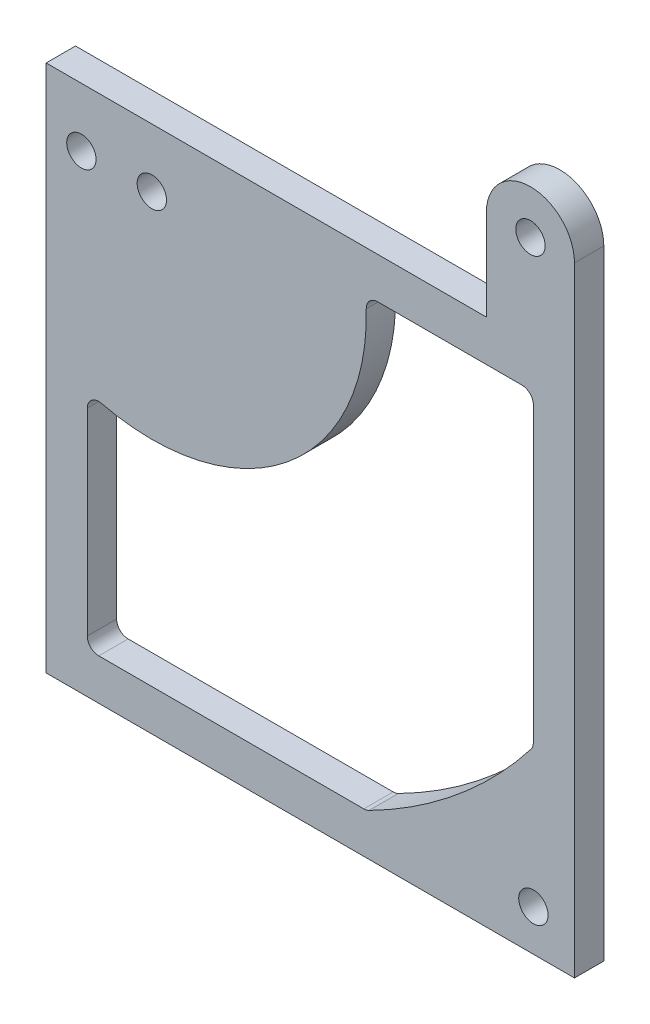
SolidWorks part; units mm, degrees
ref_plane "Front Plane" through (0, 0, 0) normal (0, 0, 1) x (1, 0, 0)
ref_plane "Top Plane" through (0, 0, 0) normal (0, 1, 0) x (1, 0, 0)
ref_plane "Right Plane" through (0, 0, 0) normal (1, 0, 0) x (0, 0, -1)
sketch "Sketch1" plane through (0, 0, 0) normal (0, 0, 1) x (1, 0, 0)
  line L1 (-57.15, -57.15) -> (57.15, -57.15)
  line L2 (-57.15, -57.15) -> (-57.15, 57.15)
  line L3 (-57.15, 57.15) -> (38.1, 57.15)
  line L4 (57.15, -57.15) -> (57.15, 76.835)
  line L5 (57.15, -57.15) -> (-57.15, 57.15) construction
  line L19 (47.625, 76.835) -> (47.625, 48.26) construction
  line L22 (38.1, 76.835) -> (38.1, 57.15)
  line L24 (-45.7715, -48.2506) -> (11.5718, -48.2506)
  line L25 (-48.26, -45.7621) -> (-48.26, -3.0766)
  line L27 (48.26, -17.4506) -> (48.26, 45.7715)
  line L30 (14.5859, 48.26) -> (45.7715, 48.26)
  line L31 (48.26, -17.4506) -> (48.26, -48.2506) construction
  line L32 (11.5718, -48.2506) -> (48.26, -48.2506) construction
  circle A17 centre (-49.53, 44.45) radius 3.175
  circle A18 centre (-34.29, 44.45) radius 3.175
  arc A34 (-45.1872, -0.6577) -> (12.0984, 45.7043) centre (-34.29, 44.45) ccw
  arc A36 (12.6995, -47.9804) -> (47.7402, -18.9727) centre (-34.29, 44.45) ccw
  arc A37 (-45.1872, -0.6577) -> (-48.26, -3.0766) centre (-45.7715, -3.0766) ccw
  arc A38 (-45.7715, -48.2506) -> (-48.26, -45.7621) centre (-45.7715, -45.7621) cw
  arc A39 (12.6995, -47.9804) -> (11.5718, -48.2506) centre (11.5718, -45.7621) cw
  arc A40 (48.26, -17.4506) -> (47.7402, -18.9727) centre (45.7715, -17.4506) cw
  arc A41 (45.7715, 48.26) -> (48.26, 45.7715) centre (45.7715, 45.7715) cw
  arc A42 (12.0984, 45.7043) -> (14.5859, 48.26) centre (14.5859, 45.7715) cw
  circle A44 centre (48.26, -48.2506) radius 3.175
  circle A45 centre (47.625, 76.835) radius 3.175
  arc A46 (38.1, 76.835) -> (57.15, 76.835) centre (47.625, 76.835) cw
  point P0 (0, 0)
  point P16 (0, 0)
  dimension "D4" = 6.35
  dimension "D5" = 6.35
  dimension "D6" = 8.89
  dimension "D9" = 6.35
  dimension "D11" = 114.3
  dimension "D12" = 6.35
  dimension "D16" = 114.3
  dimension "D10" = 6.35
  dimension "D17" = 103.6889
  dimension "D18" = 46.4053
  dimension "D1" = 7.62
  dimension "D2" = 8.89
  dimension "D3" = 12.7
  dimension "D7" = 22.86
  dimension "D8" = 12.7
  dimension "D14" = 8.8994
  dimension "D15" = 8.89
  dimension "D19" = 28.575
extrude "Boss-Extrude1" add sketch "Sketch1" along normal mid plane 6.35
